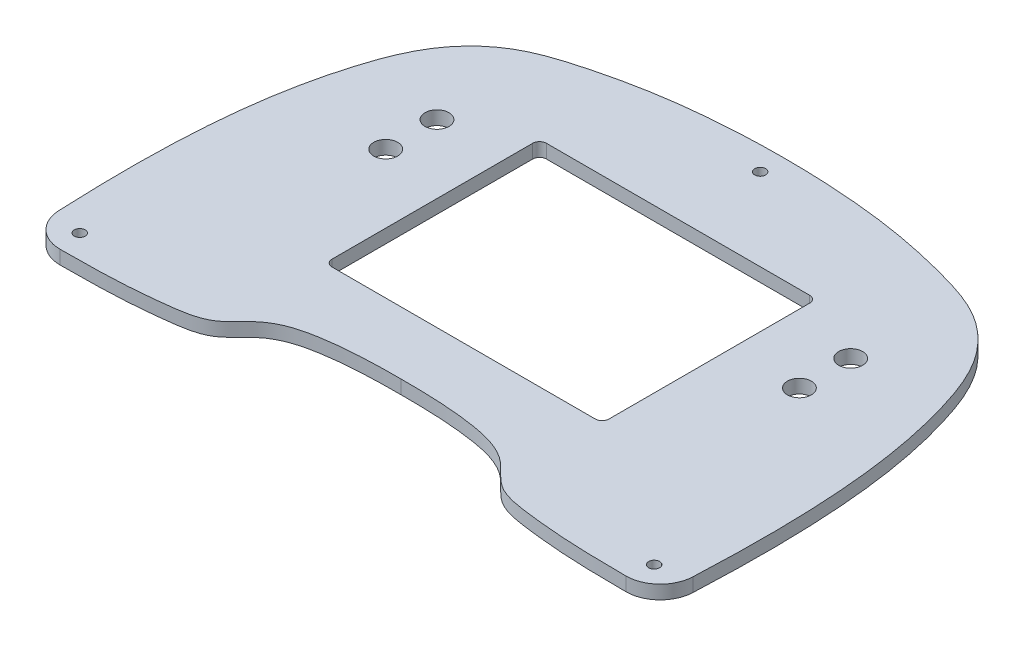
SolidWorks part; units mm, degrees
ref_plane "Front Plane" through (0, 0, 0) normal (0, 0, 1) x (1, 0, 0)
ref_plane "Top Plane" through (0, 0, 0) normal (0, 1, 0) x (1, 0, 0)
ref_plane "Right Plane" through (0, 0, 0) normal (1, 0, 0) x (0, 0, -1)
sketch "Sketch1" plane through (0, 0, 0) normal (0, 1, 0) x (1, 0, 0)
  line L1 (-120, 155) -> (120, 155)
  line L2 (-120, 155) -> (-120, -155)
  line L3 (-120, -155) -> (120, -155)
  line L4 (120, 155) -> (120, -155)
  point P4 (0, 155)
  point P6 (-120, 0)
  dimension "D1" = 240
  dimension "D2" = 310
extrude "Boss-Extrude1" add sketch "Sketch1" along normal blind 4 contours L2 L1 L4 L3
sketch "Sketch2" plane through (0, 4, 0) normal (0, 1, 0) x (1, 0, 0)
  line L0 (-120, 155) -> (120, 155) construction
  line L1 (-120, 0) -> (120, 0)
  line L2 (-120, 155) -> (-120, -155) construction
  circle B0 centre (49, -30) radius 1.75
  circle B1 centre (-49, -30) radius 1.75
  circle B2 centre (-88.957, -132.3382) radius 1.75
  circle B3 centre (0, -146) radius 1.75
  circle B4 centre (88.957, -132.3382) radius 1.75
  circle B5 centre (110.4185, 44.9345) radius 1.75
  circle B6 centre (88.957, 132.3382) radius 1.75
  circle B7 centre (0, 146) radius 1.75
  circle B8 centre (-88.957, 132.3382) radius 1.75
  circle B9 centre (-110.4185, 44.9345) radius 1.75
  spline B10 degree 3 poles (0, 155) (30.5722, 155) (80.3433, 153.7333) (119.2212, 117.6544) (120, 45.41) (120, 0) knots 0 0 0 0 0.458017 0.558017 1 1 1 1
  spline B11 degree 3 poles (0, 155) (-30.5722, 155) (-80.3433, 153.7333) (-119.2212, 117.6544) (-120, 45.41) (-120, 0) knots 0 0 0 0 0.458017 0.558017 1 1 1 1
  spline B12 degree 3 poles (0, -155) (30.5722, -155) (80.3433, -153.7333) (119.2212, -117.6544) (120, -45.41) (120, 0) knots 0 0 0 0 0.458017 0.558017 1 1 1 1
  spline B13 degree 3 poles (0, -155) (-30.5722, -155) (-80.3433, -153.7333) (-119.2212, -117.6544) (-120, -45.41) (-120, 0) knots 0 0 0 0 0.458017 0.558017 1 1 1 1
  line M2 (-120, -155) -> (120, -155)
  line M3 (120, -155) -> (120, 155)
  line M4 (120, 155) -> (-120, 155)
  line M5 (-120, 155) -> (-120, -155)
sketch_block_instance "Base-2-F1-1"
sketch_block "Base-2-F1"
extrude "Cut-Extrude1" cut sketch "Sketch2" against normal up to next contours B11 M4 M5 | B10 M4 M3 | B12 M2 M3 | B13 M2 M5 | B8 | B7 | B6 | B9 | B1 | B0 | B2 | B3 | B4 | B5
sketch "Sketch3" plane through (0, 4, 0) normal (0, 1, 0) x (1, 0, 0)
  line L1 (-120, 0) -> (120, 0)
  line L2 (-120, 0) -> (-120, -155)
  line L3 (-120, -155) -> (120, -155)
  line L4 (120, 0) -> (120, -155)
  line L5 (-120, 0) -> (120, 0)
  line L6 (-120, 0) -> (-120, 5)
  line L7 (-120, 5) -> (120, 5)
  line L8 (120, 0) -> (120, 5)
  point P9 (0, 5)
  circle M6 centre (88.957, -132.3382) radius 1.75
  circle M7 centre (0, -146) radius 1.75
  circle M11 centre (-49, -30) radius 1.75
  circle M12 centre (49, -30) radius 1.75
  circle M13 centre (-88.957, -132.3382) radius 1.75
  spline M15 degree 3 poles (0, 155) (-30.5722, 155) (-80.3433, 153.7333) (-119.2212, 117.6544) (-120, 45.41) (-120, 0) knots 0 0 0 0 0.458017 0.558017 1 1 1 1
  spline M16 degree 3 poles (-120, 0) (-120, -45.41) (-119.2212, -117.6544) (-80.3433, -153.7333) (-30.5722, -155) (0, -155) knots 0 0 0 0 0.441983 0.541983 1 1 1 1
  spline M17 degree 3 poles (0, -155) (30.5722, -155) (80.3433, -153.7333) (119.2212, -117.6544) (120, -45.41) (120, 0) knots 0 0 0 0 0.458017 0.558017 1 1 1 1
  spline M18 degree 3 poles (120, 0) (120, 45.41) (119.2212, 117.6544) (80.3433, 153.7333) (30.5722, 155) (0, 155) knots 0 0 0 0 0.441983 0.541983 1 1 1 1
  dimension "D1" = 155
  dimension "D2" = 5
extrude "Cut-Extrude2" cut sketch "Sketch3" against normal up to next contours L1 M16 M17 M6 M12 M13 M11 M7 | L7 L1 M15 M18
fillet "Fillet3" radius 3 2 edges
sketch "Sketch4" plane through (0, 4, 0) normal (0, 1, 0) x (1, 0, 0)
  line L0 (0, 5) -> (0, 144.25) construction
  line L1 (-54.5, 120.415) -> (-54.5, 27.625) construction
  line L2 (-57.5, 24.625) -> (-86.789, 24.625) construction
  line L3 (54.5, 120.415) -> (54.5, 27.625) construction
  line L4 (57.5, 24.625) -> (86.789, 24.625) construction
  line L5 (-116.9911, 5) -> (116.9911, 5) construction
  line L7 (-116.9911, 5) -> (116.9911, 5)
  circle A0 centre (0, 146) radius 1.75 construction
  arc A1 (-54.5, 120.415) -> (-58.1637, 123.3407) centre (-57.5, 120.415) ccw construction
  arc A2 (-54.5, 27.625) -> (-57.5, 24.625) centre (-57.5, 27.625) cw construction
  arc A3 (-86.789, 24.625) -> (-89.7877, 27.5373) centre (-86.789, 27.625) cw construction
  arc A4 (54.5, 120.415) -> (58.1637, 123.3407) centre (57.5, 120.415) cw
  arc A5 (86.789, 24.625) -> (89.7877, 27.5373) centre (86.789, 27.625) ccw construction
  arc A6 (54.5, 27.625) -> (57.5, 24.625) centre (57.5, 27.625) ccw construction
  circle A8 centre (0, 132) radius 1.6
  arc A10 (-119.9911, 8.0075) -> (-116.9911, 5) centre (-116.9911, 8) ccw construction
  arc A11 (116.9911, 5) -> (119.9911, 8.0075) centre (116.9911, 8) ccw construction
  arc A12 (-119.9911, 8.0075) -> (-116.9911, 5) centre (-116.9911, 8) ccw
  arc A13 (116.9911, 5) -> (119.9911, 8.0075) centre (116.9911, 8) ccw
  spline S0 degree 3 poles (-58.1637, 123.3407) (-67.2409, 121.2816) (-77.0217, 114.715) (-85.2116, 91.8938) (-89.0656, 63.3647) (-90.1983, 41.5749) (-89.7877, 27.5373) knots 0.021021 0.021021 0.021021 0.021021 0.204024 0.379971 0.619261 0.974387 0.974387 0.974387 0.974387 construction
  spline S1 degree 3 poles (58.1637, 123.3407) (67.2409, 121.2816) (77.0217, 114.715) (85.2116, 91.8938) (89.0656, 63.3647) (90.1983, 41.5749) (89.7877, 27.5373) knots 0.021021 0.021021 0.021021 0.021021 0.204024 0.379971 0.619261 0.974387 0.974387 0.974387 0.974387 construction
  spline S2 degree 3 poles (2832.9104, 1141.6728) (-715.0695, -90.7684) (0.5711, 227.7625) (185.9079, 55.7686) (-78.3221, -939.6313) (842.9767, 2919.0484) knots -2.051868 -2.051868 -2.051868 -2.051868 0.458017 0.558017 2.715289 2.715289 2.715289 2.715289 only from (0, 155) to (119.9911, 8.0075) construction
  spline S3 degree 3 poles (-2832.9104, 1141.6728) (715.0695, -90.7684) (-0.5711, 227.7625) (-185.9079, 55.7686) (78.3221, -939.6313) (-842.9767, 2919.0484) knots -2.051868 -2.051868 -2.051868 -2.051868 0.458017 0.558017 2.715289 2.715289 2.715289 2.715289 only from (0, 155) to (-119.9911, 8.0075) construction
  spline S4 degree 3 poles (0, 155) (30.5722, 155) (80.3433, 153.7333) (118.2271, 118.5769) (119.8813, 52.1095) (119.9911, 8.0075) knots 0 0 0 0 0.458017 0.558017 0.97443 0.97443 0.97443 0.97443
  spline S5 degree 3 poles (0, 155) (-30.5722, 155) (-80.3433, 153.7333) (-118.2271, 118.5769) (-119.8813, 52.1095) (-119.9911, 8.0075) knots 0 0 0 0 0.458017 0.558017 0.97443 0.97443 0.97443 0.97443
  spline S6 degree 3 poles (-92.2335, 10) (-93.109, 24.4617) (-94.1413, 55.9294) (-89.8488, 89.0425) (-82.7766, 109.2192) (-77.5058, 118.8792) (-67.5607, 127.9642) (-51.2025, 133.2045) (-28.9563, 138.0005) (-10.5009, 139) (0, 139) knots 0.048683 0.048683 0.048683 0.048683 0.273512 0.499349 0.541604 0.589205 0.661189 0.734095 0.840041 1 1 1 1
  spline S7 degree 3 poles (-92.2335, 10) (-80.6643, 10) (-67.3798, 9.833) (-50.8213, 11.7564) (-41.6876, 13.0928) (-34.6105, 23.0328) (-19.1579, 26.7733) (-6.7173, 27) (0, 27) knots 0 0 0 0 0.354855 0.417369 0.52509 0.626101 0.77445 1 1 1 1
  spline S8 degree 3 poles (92.2335, 10) (93.109, 24.4617) (94.1413, 55.9294) (89.8488, 89.0425) (82.7766, 109.2192) (77.5058, 118.8792) (67.5607, 127.9642) (51.2025, 133.2045) (28.9563, 138.0005) (10.5009, 139) (0, 139) knots 0.048683 0.048683 0.048683 0.048683 0.273512 0.499349 0.541604 0.589205 0.661189 0.734095 0.840041 1 1 1 1
  spline S9 degree 3 poles (92.2335, 10) (80.6643, 10) (67.3798, 9.833) (50.8213, 11.7564) (41.6876, 13.0928) (34.6105, 23.0328) (19.1579, 26.7733) (6.7173, 27) (0, 27) knots 0 0 0 0 0.354855 0.417369 0.52509 0.626101 0.77445 1 1 1 1
  point P0 (0, 24.625)
  point P5 (39.5, 74.625)
  point P6 (0, 74.625)
  point P21 (-54.5, 24.625)
  point P39 (0, 146)
  line B0 (-39.5, 124.625) -> (39.5, 124.625) construction
  line B1 (-39.5, 124.625) -> (-39.5, 24.625) construction
  line B2 (-39.5, 24.625) -> (39.5, 24.625) construction
  line B3 (39.5, 124.625) -> (39.5, 24.625) construction
  circle B4 centre (35.5, 120.625) radius 1.35
  circle B5 centre (-22.5, 120.625) radius 1.35
  circle B6 centre (-22.5, 34.625) radius 1.35
  circle B7 centre (35.5, 34.625) radius 1.35
  dimension "D3" = 3
  dimension "D2" = 3.2
  dimension "D1" = 15
  dimension "D4" = 14
  dimension "D5" = 5
  dimension "D6" = 22
sketch_block_instance "JETSON-NANO-1"
sketch_block "JETSON-NANO"
extrude "Cut-Extrude3" cut sketch "Sketch4" against normal blind 5
fillet "Fillet4" radius 10 2 edges at (92.2335, 2, -10) (-92.2335, 2, -10)
sketch "Sketch5" plane through (0, 4, 0) normal (0, 1, 0) x (1, 0, 0)
  line L0 (0, 132) -> (0, 17) construction
  line L1 (-84, 17) -> (84, 17) construction
  circle A0 centre (-84, 17) radius 1.6
  circle A1 centre (84, 17) radius 1.6
  point P6 (0, 17)
  dimension "D1" = 3.2
  dimension "D2" = 17
  dimension "D3" = 168
extrude "Cut-Extrude4" cut sketch "Sketch5" against normal through all
sketch "Sketch6" plane through (0, 4, 0) normal (0, 1, 0) x (1, 0, 0)
  line L0 (-2.9, 107.97) -> (-2.9, 45.27)
  line L1 (-0.9, 105.97) -> (38.5, 105.97) construction
  line L2 (-0.9, 105.97) -> (-0.9, 47.27) construction
  line L3 (-0.9, 47.27) -> (38.5, 47.27) construction
  line L4 (38.5, 105.97) -> (38.5, 47.27) construction
  line L5 (-2.9, 45.27) -> (40.5, 45.27)
  line L6 (40.5, 107.97) -> (40.5, 45.27)
  line L7 (-2.9, 107.97) -> (40.5, 107.97)
  line L8 (0, 132) -> (0, 0) construction
  line L9 (2.9, 107.97) -> (-40.5, 107.97)
  line L10 (-40.5, 107.97) -> (-40.5, 45.27)
  line L11 (2.9, 45.27) -> (-40.5, 45.27)
  line L12 (2.9, 107.97) -> (2.9, 45.27)
  point P4 (0, 132)
  point P5 (84, 17)
  dimension "D1" = 39.4
  dimension "D2" = 58.7
  dimension "D3" = 45.5
  dimension "D4" = 26.03
  dimension "D5" = 2
extrude "Cut-Extrude5" cut sketch "Sketch6" against normal through all contours L11 L0 L9 L10 | L12 L7 L0 L5 | L7 L12 L5 L6
sketch "Sketch7" plane through (0, 4, 0) normal (0, 1, 0) x (1, 0, 0)
  line L0 (40.5, 107.97) -> (-40.5, 107.97) construction
  line L5 (40.5, 107.97) -> (40.5, 45.27) construction
  line L6 (0, 139) -> (0, 0) construction
  circle A0 centre (60.5, 97.97) radius 3.5
  circle A2 centre (-60.5, 97.97) radius 3.5
  circle A4 centre (60.5, 82.97) radius 3.5
  circle A5 centre (-60.5, 82.97) radius 3.5
  dimension "D1" = 7
  dimension "D2" = 10
  dimension "D3" = 20
  dimension "D4" = 2
extrude "Cut-Extrude6" cut sketch "Sketch7" against normal through all
fillet "Fillet5" radius 2 4 edges at (-40.5, 2, -45.27) (-40.5, 2, -107.97) (40.5, 2, -45.27) (40.5, 2, -107.97)
